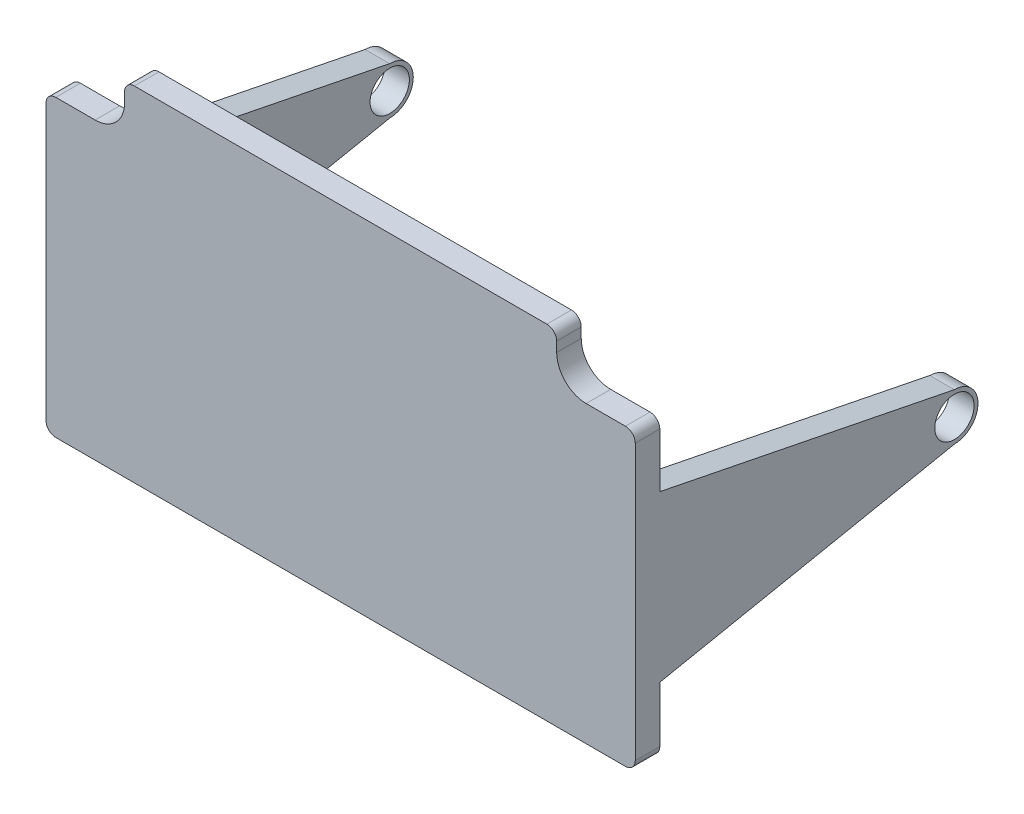
SolidWorks part; units mm, degrees
ref_plane "Alzado" through (0, 0, 0) normal (0, 0, 1) x (1, 0, 0)
ref_plane "Planta" through (0, 0, 0) normal (0, 1, 0) x (1, 0, 0)
ref_plane "Vista lateral" through (0, 0, 0) normal (1, 0, 0) x (0, 0, -1)
sketch "Croquis2" plane through (0, 0, 0) normal (0, 0, 1) x (1, 0, 0)
  line L0 (-30, 15) -> (-25, 15) construction
  line L1 (30, -15) -> (-30, -15)
  line L2 (30, -15) -> (30, 15)
  line L3 (30, 15) -> (25, 15)
  line L4 (-30, -15) -> (-30, 15)
  line L5 (30, -15) -> (-30, 15) construction
  line L6 (30, 15) -> (-30, -15) construction
  line L7 (30, 15) -> (25, 15) construction
  line L8 (-22, 18) -> (-22, 20)
  line L9 (-22, 20) -> (22, 20)
  line L10 (22, 20) -> (22, 18)
  line L11 (-25, 15) -> (-30, 15)
  arc A0 (25, 15) -> (22, 18) centre (25, 18) cw
  arc A1 (-25, 15) -> (-22, 18) centre (-25, 18) ccw
  point P0 (0, 0)
  point P12 (22, 15)
  point P15 (-22, 15)
  dimension "D6" = 3
  dimension "D1" = 60
  dimension "D2" = 30
  dimension "D3" = 8
  dimension "D4" = 8
  dimension "D5" = 5
extrude "Saliente-Extruir1" add sketch "Croquis2" against normal blind 2.5
fillet "Redondeo1" radius 1 2 edges at (22, 20, -1.25) (-22, 20, -1.25)
fillet "Redondeo2" radius 1 4 edges at (-30, 15, -1.25) (-30, -15, -1.25) (30, -15, -1.25) (30, 15, -1.25)
sketch "Croquis3" plane through (0, 0, -2.5) normal (0, 0, -1) x (-1, 0, 0)
  line L0 (-30, 14) -> (-30, 0) construction
  line L1 (-30, -14) -> (-30, 14) construction
  line L2 (30, 2.4749) -> (27.5, 2.4749)
  line L3 (-27.5, -2.3327) -> (-30, -2.3327)
  line L4 (-30, -2.3327) -> (-30, 2.4749)
  line L5 (-30, 2.4749) -> (-27.5, 2.4749)
  line L6 (-27.5, 2.4749) -> (-27.5, -2.3327)
  line L7 (30, 14) -> (30, -14) construction
  line L8 (27.5, 2.4749) -> (27.5, -2.3327)
  line L9 (27.5, -2.3327) -> (30, -2.3327)
  line L10 (30, -2.3327) -> (30, 2.4749)
  dimension "D1" = 2.5
  dimension "D2" = 2.5
extrude "Saliente-Extruir2" add sketch "Croquis3" along normal blind 30
sketch "Croquis4" plane through (30, 0, 0) normal (1, 0, 0) x (0, 0, -1)
  line L0 (32.5, -2.3327) -> (2.5, -8.3327)
  line L2 (2.5, 2.4749) -> (2.5, 8.4749) construction
  line L3 (2.5, 2.4749) -> (2.5, 14) construction
  line L4 (2.5, 2.4749) -> (2.5, 8.4749)
  line L5 (2.5, 8.4749) -> (32.5, 2.4749)
  line L6 (2.5, -14) -> (2.5, -2.3327) construction
  line L7 (32.5, -2.3327) -> (32.5, -2.3289)
  line L11 (2.5, -8.3327) -> (2.5, 2.4749)
  line L12 (2.5, -8.3327) -> (2.5, -2.3327) construction
  line L13 (32.5, 2.4749) -> (32.5, 2.4711) construction
  line L14 (32.5, 0.0711) -> (29.766, 0.0711) construction
  line L15 (32.5, 2.4711) -> (32.5, 2.4749)
  arc A0 (32.5, -2.3289) -> (32.5, 2.4711) centre (32.5, 0.0711) ccw
  dimension "D1" = 6
  dimension "D2" = 6
  dimension "D3" = 4.8076
extrude "Saliente-Extruir3" add sketch "Croquis4" against normal blind 2.5
sketch "Croquis5" plane through (-30, 0, 0) normal (-1, 0, 0) x (0, 0, 1)
  line L0 (-2.5, 8.4749) -> (-2.5, -8.3327)
  line L1 (-2.5, 14) -> (-2.5, 2.4749) construction
  line L2 (-2.5, 8.4749) -> (-32.5, 2.4749)
  line L3 (-32.5, 2.4749) -> (-32.5, 2.4711)
  line L4 (-32.5, -2.3327) -> (-2.5, -8.3327)
  line L5 (-2.5, -2.3327) -> (-2.5, -14) construction
  line L7 (-32.5, 2.4749) -> (-32.5, 2.4711) construction
  line L8 (-32.5, -2.3289) -> (-32.5, -2.3327)
  arc A0 (-32.5, 2.4711) -> (-32.5, -2.3289) centre (-32.5, 0.0711) ccw
  dimension "D2" = 6
extrude "Saliente-Extruir4" add sketch "Croquis5" against normal blind 2.5
sketch "Croquis6" plane through (30, 0, 0) normal (1, 0, 0) x (0, 0, -1)
  line L0 (0, 0) -> (32.5, 0.0711) construction
  circle A0 centre (32.5, 0.0711) radius 2
extrude "Cortar-Extruir1" cut sketch "Croquis6" against normal blind 100
